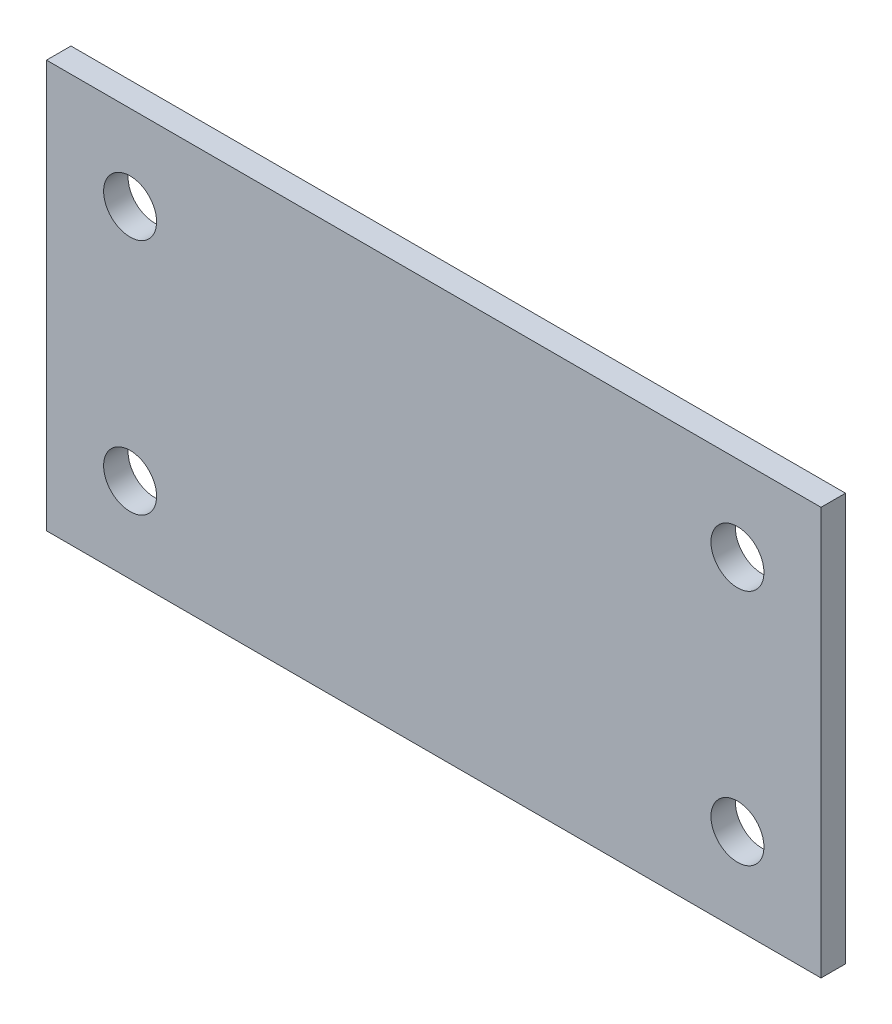
SolidWorks part; units mm, degrees
ref_plane "前视基准面" through (0, 0, 0) normal (0, 0, 1) x (1, 0, 0)
ref_plane "上视基准面" through (0, 0, 0) normal (0, 1, 0) x (1, 0, 0)
ref_plane "右视基准面" through (0, 0, 0) normal (1, 0, 0) x (0, 0, -1)
sketch "草图1" plane through (0, 0, 0) normal (0, 0, 1) x (1, 0, 0)
  line L1 (0, 0) -> (380, 0)
  line L2 (0, 0) -> (0, 200)
  line L3 (0, 200) -> (380, 200)
  line L4 (380, 0) -> (380, 200)
  dimension "D1" = 380
  dimension "D2" = 200
extrude "凸台-拉伸1" add sketch "草图1" along normal blind 12
sketch "草图2" plane through (0, 0, 12) normal (0, 0, 1) x (1, 0, 0)
  line L0 (0, 0) -> (44245.9111, 23287.3216) construction
  line L1 (0, 200) -> (44245.9111, -23087.3216) construction
  line L2 (190, 100) -> (9.1, 29.2) construction
  line L3 (9.1, 29.2) -> (190, 29.2) construction
  line L4 (190, 29.2) -> (190, 100) construction
  line L5 (380, 0) -> (380, 200) construction
  line L6 (0, 0) -> (380, 0) construction
  circle A0 centre (41.0048, 41.6868) radius 13
  dimension "D3" = 26
  dimension "D1" = 70.8
  dimension "D2" = 180.9
  dimension "D4" = 160
extrude "切除-拉伸1" cut sketch "草图2" against normal through all
ref_plane "基准面1" through (0, 100, 0) normal (0, 1, 0) x (1, 0, 0)
ref_plane "基准面2" through (190, 0, 0) normal (1, 0, 0) x (0, 0, -1)
mirror "镜向1" about plane through (0, 100, 0) normal (0, 1, 0) of "切除-拉伸1"
mirror "镜向2" about plane through (190, 0, 0) normal (1, 0, 0) of "镜向1", "切除-拉伸1"
